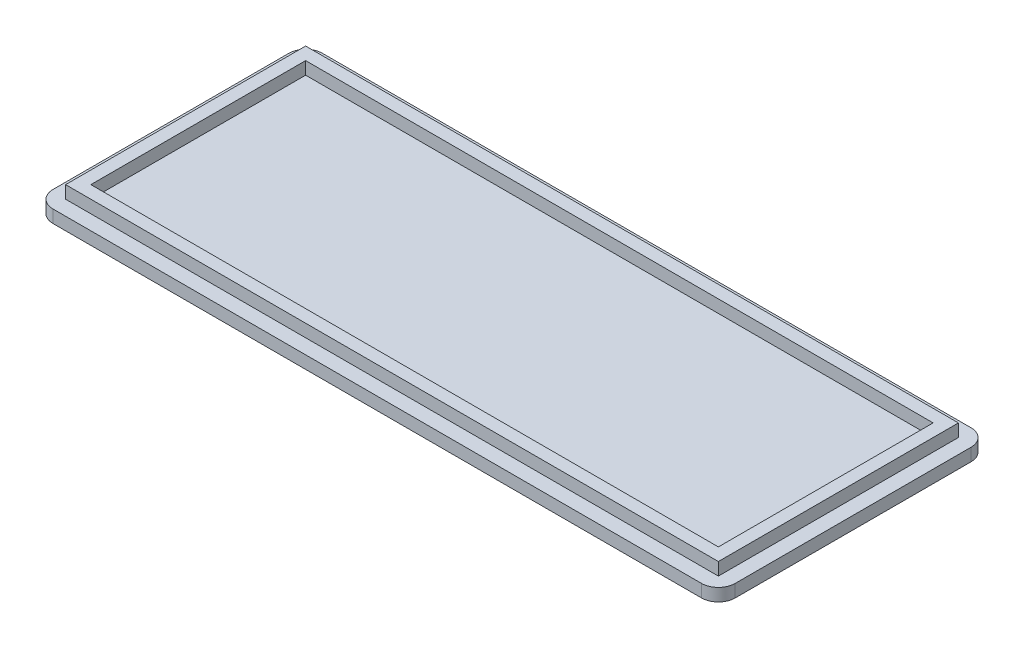
SolidWorks part; units mm, degrees
ref_plane "Front Plane" through (0, 0, 0) normal (0, 0, 1) x (1, 0, 0)
ref_plane "Top Plane" through (0, 0, 0) normal (0, 1, 0) x (1, 0, 0)
ref_plane "Right Plane" through (0, 0, 0) normal (1, 0, 0) x (0, 0, -1)
sketch "Sketch1" plane through (0, 0, 0) normal (0, 1, 0) x (1, 0, 0)
  line L2 (-76.5469, -86.2908) -> (-153.5469, -86.2908)
  line L3 (-74.5469, -84.2908) -> (-74.5469, -56.2908)
  line L4 (-76.5469, -54.2908) -> (-153.5469, -54.2908)
  line L5 (-155.5469, -84.2908) -> (-155.5469, -56.2908)
  arc A0 (-76.5469, -86.2908) -> (-74.5469, -84.2908) centre (-76.5469, -84.2908) ccw
  arc A1 (-74.5469, -56.2908) -> (-76.5469, -54.2908) centre (-76.5469, -56.2908) ccw
  arc A2 (-153.5469, -54.2908) -> (-155.5469, -56.2908) centre (-153.5469, -56.2908) ccw
  arc A3 (-153.5469, -86.2908) -> (-155.5469, -84.2908) centre (-153.5469, -84.2908) cw
  point P3 (-74.5469, -86.2908)
  point P9 (-74.5469, -54.2908)
  point P14 (-155.5469, -86.2908)
  dimension "D3" = 2
  dimension "D1" = 81
  dimension "D2" = 32
extrude "Boss-Extrude1" add sketch "Sketch1" along normal blind 1.5
sketch "Sketch2" plane through (0, 1.5, 0) normal (0, 1, 0) x (1, 0, 0)
  line L0 (-155.5469, -56.2908) -> (-155.5469, -84.2908) construction
  line L1 (-153.7969, -56.0408) -> (-76.2969, -56.0408)
  line L2 (-153.7969, -56.0408) -> (-153.7969, -84.5408)
  line L3 (-153.7969, -84.5408) -> (-76.2969, -84.5408)
  line L4 (-76.2969, -56.0408) -> (-76.2969, -84.5408)
  line L5 (-152.2969, -57.5408) -> (-77.7969, -57.5408)
  line L6 (-152.2969, -57.5408) -> (-152.2969, -83.0408)
  line L7 (-152.2969, -83.0408) -> (-77.7969, -83.0408)
  line L8 (-77.7969, -57.5408) -> (-77.7969, -83.0408)
  line L12 (-153.5469, -86.2908) -> (-76.5469, -86.2908) construction
  dimension "D1" = 1.5
  dimension "D2" = 1.5
  dimension "D3" = 1.5
  dimension "D4" = 1.5
  dimension "D5" = 28.5
  dimension "D6" = 77.5
  dimension "D7" = 1.75
  dimension "D8" = 1.75
extrude "Boss-Extrude2" add sketch "Sketch2" along normal blind 1.5
